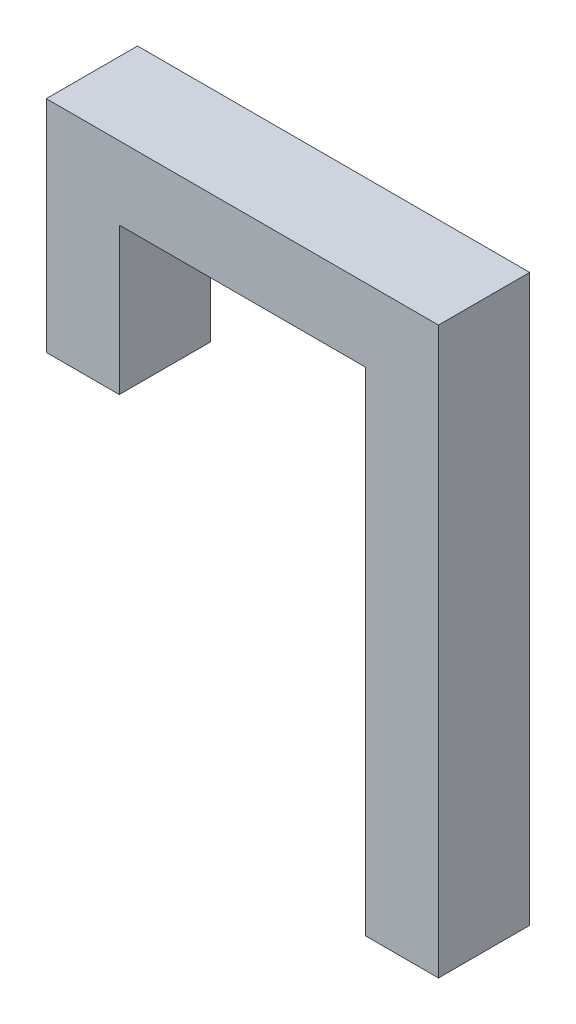
SolidWorks part; units mm, degrees
ref_plane "Front Plane" through (0, 0, 0) normal (0, 0, 1) x (1, 0, 0)
ref_plane "Top Plane" through (0, 0, 0) normal (0, 1, 0) x (1, 0, 0)
ref_plane "Right Plane" through (0, 0, 0) normal (1, 0, 0) x (0, 0, -1)
sketch "Sketch1" plane through (0, 0, 0) normal (0, 0, 1) x (1, 0, 0)
  line L0 (0, 0) -> (13.5, 0)
  line L1 (13.5, 0) -> (13.5, -27)
  line L2 (0, 0) -> (0, -8.05)
  line L3 (0, -8.05) -> (-4, -8.05)
  line L4 (-4, -8.05) -> (-4, 4)
  line L5 (-4, 4) -> (17.5, 4)
  line L6 (17.5, 4) -> (17.5, -27)
  line L7 (17.5, -27) -> (13.5, -27)
  dimension "D1" = 13.5
  dimension "D2" = 27
  dimension "D3" = 8.05
  dimension "D4" = 4
  dimension "D5" = 12.05
  dimension "D6" = 21.5
  dimension "D8" = 4
extrude "Boss-Extrude1" add sketch "Sketch1" along normal blind 5
